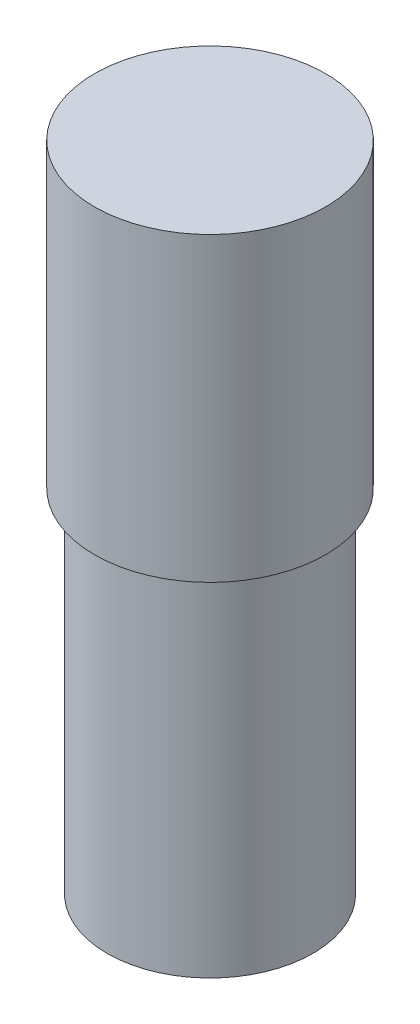
SolidWorks part; units mm, degrees
ref_plane "Front Plane" through (0, 0, 0) normal (0, 0, 1) x (1, 0, 0)
ref_plane "Top Plane" through (0, 0, 0) normal (0, 1, 0) x (1, 0, 0)
ref_plane "Right Plane" through (0, 0, 0) normal (1, 0, 0) x (0, 0, -1)
other "Configuration Table"
sketch "草图1" plane through (0, 0, 0) normal (0, 1, 0) x (1, 0, 0)
  circle A0 centre (0, 0) radius 2.05
extrude "凸台-拉伸1" add sketch "草图1" along normal blind 7
sketch "草图2" plane through (0, 7, 0) normal (0, 1, 0) x (1, 0, 0)
  circle A0 centre (0, 0) radius 2.3
extrude "凸台-拉伸2" add sketch "草图2" along normal blind 6
